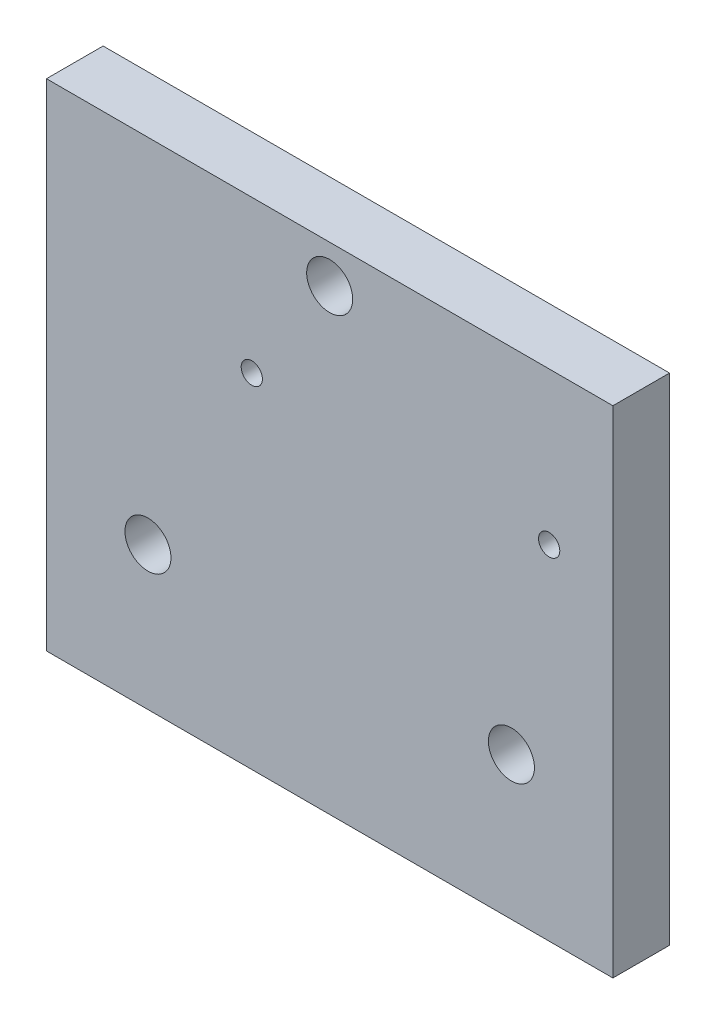
SolidWorks part; units mm, degrees
ref_plane "Front Plane" through (0, 0, 0) normal (0, 0, 1) x (1, 0, 0)
ref_plane "Top Plane" through (0, 0, 0) normal (0, 1, 0) x (1, 0, 0)
ref_plane "Right Plane" through (0, 0, 0) normal (1, 0, 0) x (0, 0, -1)
sketch "Sketch1" plane through (0, 0, 0) normal (0, 0, 1) x (1, 0, 0)
  line L1 (0, 0) -> (-160, 0)
  line L2 (0, 0) -> (0, -140)
  line L3 (0, -140) -> (-160, -140)
  line L4 (-160, 0) -> (-160, -140)
  dimension "D1" = 160
  dimension "D2" = 140
extrude "Boss-Extrude1" add sketch "Sketch1" along normal blind 16
sketch "Sketch2" plane through (0, 0, 16) normal (0, 0, 1) x (1, 0, 0)
  line L0 (-80, 0) -> (-80, -140) construction
  line L1 (0, 0) -> (-160, 0) construction
  line L2 (-160, -140) -> (0, -140) construction
  line L3 (-160, -70) -> (0, -70) construction
  line L4 (-80, -10.7219) -> (-131.3363, -99.639) construction
  line L5 (0, -140) -> (0, 0) construction
  line L6 (-160, 0) -> (-160, -140) construction
  line L7 (-80, -10.7219) -> (-28.6637, -99.639) construction
  line L8 (-131.3363, -99.639) -> (-28.6637, -99.639) construction
  circle A0 centre (-131.3363, -99.639) radius 6.5
  circle A1 centre (-80, -10.7219) radius 6.5
  circle A2 centre (-28.6637, -99.639) radius 6.5
  circle A4 centre (-80, -70) radius 59.2781 construction
  dimension "D1" = 13
  dimension "D2" = 118.5562
extrude "Cut-Extrude1" cut sketch "Sketch2" against normal blind 11
sketch "Sketch3" plane through (0, 0, 16) normal (0, 0, 1) x (1, 0, 0)
  line L0 (0, -140) -> (0, 0) construction
  line L1 (0, 0) -> (-160, 0) construction
  circle A0 centre (-18, -43) radius 3
  circle A1 centre (-102, -43) radius 3
  dimension "D1" = 6
  dimension "D2" = 6
  dimension "D3" = 18
  dimension "D4" = 102
  dimension "D6" = 43
  dimension "D5" = 43
extrude "Cut-Extrude2" cut sketch "Sketch3" against normal through all
